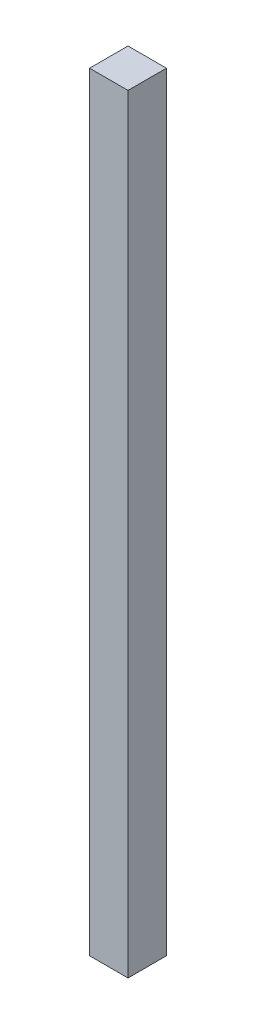
SolidWorks part; units mm, degrees
ref_plane "Front Plane" through (0, 0, 0) normal (0, 0, 1) x (1, 0, 0)
ref_plane "Top Plane" through (0, 0, 0) normal (0, 1, 0) x (1, 0, 0)
ref_plane "Right Plane" through (0, 0, 0) normal (1, 0, 0) x (0, 0, -1)
sketch "Sketch1" plane through (0, 0, 0) normal (0, 1, 0) x (1, 0, 0)
  line L1 (0, 0) -> (20, 0)
  line L2 (0, 0) -> (0, -20)
  line L3 (0, -20) -> (20, -20)
  line L4 (20, 0) -> (20, -20)
extrude "Boss-Extrude1" add sketch "Sketch1" along normal blind 400
